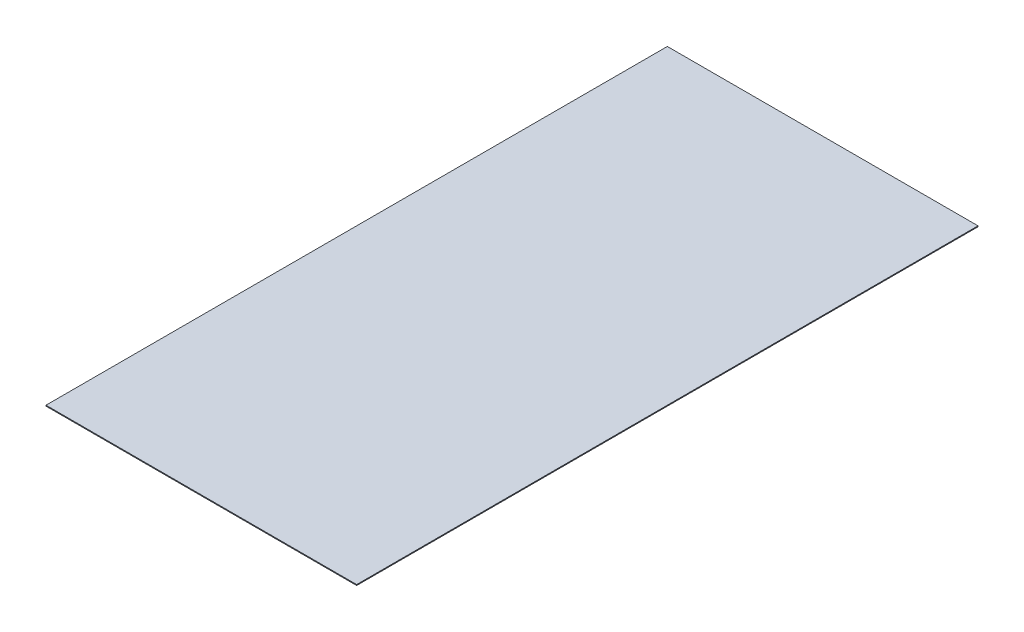
SolidWorks part; units mm, degrees
material "ASTM A36 Acero"
ref_plane "Alzado" through (0, 0, 0) normal (0, 0, 1) x (1, 0, 0)
ref_plane "Planta" through (0, 0, 0) normal (0, 1, 0) x (1, 0, 0)
ref_plane "Vista lateral" through (0, 0, 0) normal (1, 0, 0) x (0, 0, -1)
sketch "Croquis1" plane through (0, 0, 0) normal (0, 1, 0) x (1, 0, 0)
  line L1 (-609.6, -1219.2) -> (609.6, -1219.2)
  line L2 (-609.6, -1219.2) -> (-609.6, 1219.2)
  line L3 (-609.6, 1219.2) -> (609.6, 1219.2)
  line L4 (609.6, -1219.2) -> (609.6, 1219.2)
  line L5 (-609.6, -1219.2) -> (609.6, 1219.2) construction
  line L6 (-609.6, 1219.2) -> (609.6, -1219.2) construction
  point P0 (0, 0)
  dimension "D1" = 2438.4
  dimension "D2" = 1219.2
extrude "Saliente-Extruir1" add sketch "Croquis1" along normal blind 3.4
